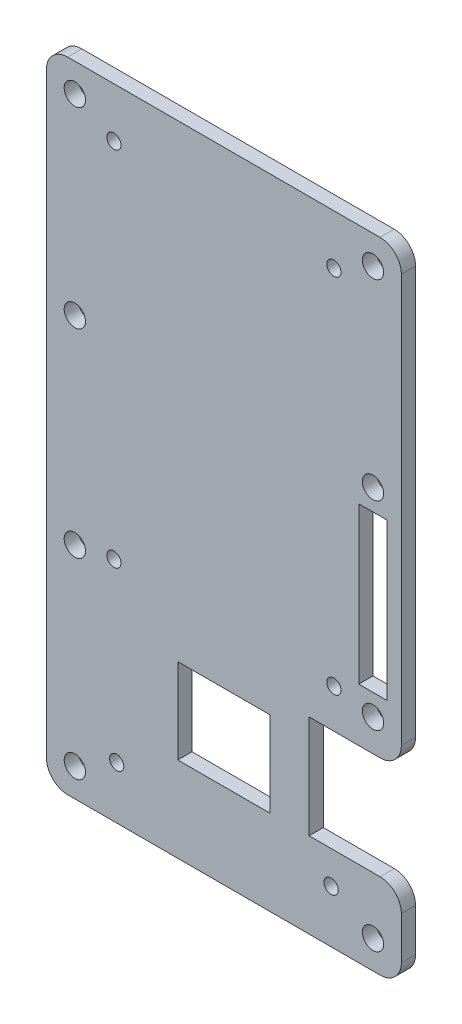
SolidWorks part; units mm, degrees
ref_plane "前视基准面" through (0, 0, 0) normal (0, 0, 1) x (1, 0, 0)
ref_plane "上视基准面" through (0, 0, 0) normal (0, 1, 0) x (1, 0, 0)
ref_plane "右视基准面" through (0, 0, 0) normal (1, 0, 0) x (0, 0, -1)
sketch "草图1" plane through (0, 0, 11.1336) normal (0, 0, 1) x (1, 0, 0)
  line L0 (-963.6089, 37.2365) -> (49036.3911, 37.2365) construction
  line L5 (54.8911, 16.2365) -> (67.8911, 16.2365)
  line L6 (54.8911, 16.2365) -> (54.8911, 4.2365)
  line L7 (54.8911, 4.2365) -> (67.8911, 4.2365)
  line L8 (67.8911, 16.2365) -> (67.8911, 4.2365)
  line L9 (36.3911, 82.2365) -> (86.3911, 82.2365)
  line L10 (36.3911, 82.2365) -> (36.3911, -7.7635)
  line L11 (36.3911, -7.7635) -> (86.3911, -7.7635)
  line L12 (86.3911, 82.2365) -> (86.3911, -7.7635)
  line L13 (73.3911, 18.7365) -> (86.3911, 18.7365)
  line L14 (73.3911, 18.7365) -> (73.3911, 4.2365)
  line L15 (73.3911, 4.2365) -> (86.3911, 4.2365)
  line L16 (86.3911, 18.7365) -> (86.3911, 4.2365)
  line L21 (80.3911, 48.2365) -> (84.3911, 48.2365)
  line L22 (80.3911, 48.2365) -> (80.3911, 26.2365)
  line L23 (80.3911, 26.2365) -> (84.3911, 26.2365)
  line L24 (84.3911, 48.2365) -> (84.3911, 26.2365)
  line L25 (61.3911, -917.7635) -> (61.3911, 49082.2365) construction
  circle A0 centre (76.4911, -0.3635) radius 1
  circle A5 centre (45.8911, 75.2365) radius 1 construction
  circle A11 centre (45.8911, 75.2365) radius 1
  circle A22 centre (76.8911, 75.2365) radius 1
  circle A23 centre (45.8911, 24.2365) radius 1
  circle A24 centre (76.8911, 24.2365) radius 1
  circle A25 centre (46.2911, -0.3635) radius 1
  point P0 (0, 0)
  point P12 (0, 0)
  point P13 (80.3911, 48.2365)
  point P42 (36.3911, 37.2365)
  point P48 (61.3911, 82.2365)
  dimension "D5" = 12
  dimension "D16" = 7
  dimension "D18" = 2
  dimension "D14" = 2
  dimension "D1" = 50
  dimension "D2" = 90
  dimension "D3" = 4
  dimension "D4" = 11
  dimension "D6" = 12
  dimension "D7" = 6.5
  dimension "D8" = 13
  dimension "D9" = 22
  dimension "D10" = 2
  dimension "D11" = 0
  dimension "D12" = 14.5
  dimension "D13" = 13
  dimension "D15" = 15.1
  dimension "D17" = 15.5
  dimension "D19" = 51
  dimension "D20" = 7.4
extrude "凸台-拉伸1" add sketch "草图1" along normal blind 2
fillet "圆角2" radius 3 6 edges at (36.3911, -7.7635, 12.1336) (36.3911, 82.2365, 12.1336) (86.3911, 82.2365, 12.1336) (86.3911, -7.7635, 12.1336) (86.3911, 4.2365, 12.1336) (86.3911, 18.7365, 12.1336)
sketch "草图2" plane through (0, 0, 13.1336) normal (0, 0, 1) x (1, 0, 0)
  line L0 (61.3911, -917.8752) -> (61.3911, 49082.1248) construction
  line L1 (-963.4271, 37.2365) -> (49036.5729, 37.2365) construction
  line L10 (86.3911, -4.7635) -> (86.3911, 1.2365)
  line L11 (86.3911, -4.7635) -> (86.3911, 1.2365)
  line L12 (86.3911, 21.7365) -> (86.3911, 79.2365)
  line L13 (86.3911, 21.7365) -> (86.3911, 79.2365)
  line L16 (36.3911, 79.2365) -> (36.3911, -4.7635)
  line L17 (39.3911, -7.7635) -> (83.3911, -7.7635)
  line L19 (83.3911, 4.2365) -> (73.3911, 4.2365)
  line L20 (73.3911, 4.2365) -> (73.3911, 18.7365)
  line L21 (73.3911, 18.7365) -> (83.3911, 18.7365)
  line L23 (83.3911, 82.2365) -> (39.3911, 82.2365)
  line L24 (36.3911, 79.2365) -> (36.3911, -4.7635)
  line L25 (39.3911, -7.7635) -> (83.3911, -7.7635)
  line L27 (83.3911, 4.2365) -> (73.3911, 4.2365)
  line L28 (73.3911, 4.2365) -> (73.3911, 18.7365)
  line L29 (73.3911, 18.7365) -> (83.3911, 18.7365)
  line L31 (83.3911, 82.2365) -> (39.3911, 82.2365)
  circle A0 centre (40.3911, 78.2365) radius 1.5
  circle A1 centre (82.3911, 78.2365) radius 1.5
  circle A2 centre (40.3911, 23.2365) radius 1.5
  circle A3 centre (82.3911, 23.2365) radius 1.5
  circle A4 centre (40.3911, 51.2365) radius 1.5
  circle A5 centre (82.3911, 51.2365) radius 1.5
  circle A6 centre (82.3911, -3.7635) radius 1.5
  circle A7 centre (40.3911, -3.7635) radius 1.5
  arc A12 (36.3911, -4.7635) -> (39.3911, -7.7635) centre (39.3911, -4.7635) ccw
  arc A13 (36.3911, -4.7635) -> (39.3911, -7.7635) centre (39.3911, -4.7635) ccw
  arc A14 (83.3911, -7.7635) -> (86.3911, -4.7635) centre (83.3911, -4.7635) ccw
  arc A15 (83.3911, -7.7635) -> (86.3911, -4.7635) centre (83.3911, -4.7635) ccw
  arc A16 (86.3911, 1.2365) -> (83.3911, 4.2365) centre (83.3911, 1.2365) ccw
  arc A17 (86.3911, 1.2365) -> (83.3911, 4.2365) centre (83.3911, 1.2365) ccw
  arc A26 (83.3911, 18.7365) -> (86.3911, 21.7365) centre (83.3911, 21.7365) ccw
  arc A27 (83.3911, 18.7365) -> (86.3911, 21.7365) centre (83.3911, 21.7365) ccw
  arc A28 (86.3911, 79.2365) -> (83.3911, 82.2365) centre (83.3911, 79.2365) ccw
  arc A29 (86.3911, 79.2365) -> (83.3911, 82.2365) centre (83.3911, 79.2365) ccw
  arc A30 (39.3911, 82.2365) -> (36.3911, 79.2365) centre (39.3911, 79.2365) ccw
  arc A31 (39.3911, 82.2365) -> (36.3911, 79.2365) centre (39.3911, 79.2365) ccw
  point P9 (61.3911, 82.2365)
  point P11 (36.3911, 37.2365)
  dimension "D2" = 3
  dimension "D3" = 4
  dimension "D4" = 4
  dimension "D1" = 0
  dimension "D5" = 2
extrude "切除-拉伸1" cut sketch "草图2" against normal through all contours A0 | A4 | A2 | A7 | A6 | A5 | A3 | A1
